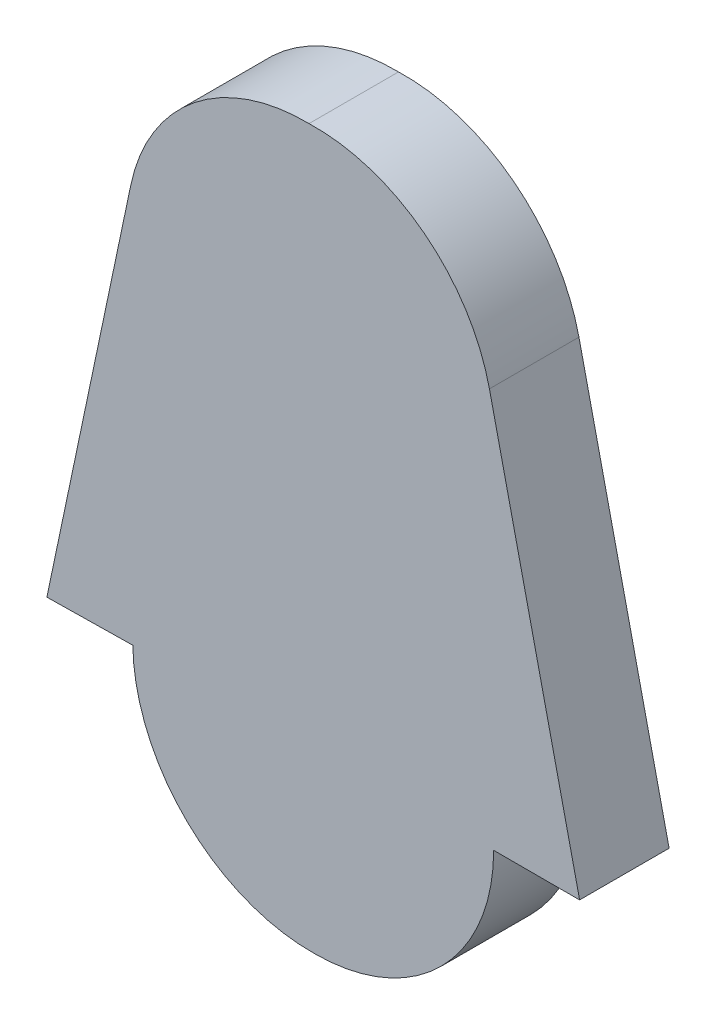
SolidWorks part; units mm, degrees
material "Plain Carbon Steel"
ref_plane "Front Plane" through (0, 0, 0) normal (0, 0, 1) x (1, 0, 0)
ref_plane "Top Plane" through (0, 0, 0) normal (0, 1, 0) x (1, 0, 0)
ref_plane "Right Plane" through (0, 0, 0) normal (1, 0, 0) x (0, 0, -1)
sketch "Sketch1" plane through (0, 0, 0) normal (0, 0, 1) x (1, 0, 0)
  line B0 (50.6598, -22.4809) -> (50.6598, -6.6059)
  line B1 (40.8052, -6.6059) -> (40.8052, -22.4809)
  line B2 (-11.4373, 39.0502) -> (-4.7473, 45.8293)
  line B3 (-4.7473, 45.8293) -> (-4.9808, 47.592)
  line B4 (-4.9808, 47.592) -> (-15.3046, 46.2245)
  line B5 (-15.3046, 46.2245) -> (-8.7339, -3.3803)
  line B6 (1.7621, -11.47) -> (46.5302, -5.8079)
  line B7 (45.5334, 6.8529) -> (5.0154, 5.583)
  line B8 (0.0223, 9.8219) -> (-2.4793, 28.7069)
  line B9 (-2.4793, 28.7069) -> (-10.7035, 33.5105)
  line B10 (-4.7473, 45.8293) -> (-2.4793, 28.7069)
  line B11 (-2.4793, 28.7069) -> (-0.2634, 29.0004)
  line B12 (-0.2634, 29.0004) -> (-2.1979, 43.6049)
  line B13 (-2.1979, 43.6049) -> (1.8812, 44.1452)
  line B14 (1.8812, 44.1452) -> (1.5477, 46.6632)
  line B15 (1.5477, 46.6632) -> (-4.7473, 45.8293)
  line B16 (55.1305, -12.1939) -> (51.9321, 1.9053)
  line B17 (37.5248, -6.9469) -> (36.3345, -12.1939)
  line B18 (36.3345, -12.1939) -> (39.3825, -12.1939)
  line B19 (52.0825, -12.1939) -> (55.1305, -12.1939)
  circle B20 centre (0, 0) radius 6.35
  arc B21 (-11.4373, 39.0502) -> (-10.7035, 33.5105) centre (-8.9193, 36.5653) ccw
  arc B22 (-8.7339, -3.3803) -> (1.7621, -11.47) centre (0.5828, -2.1462) ccw
  arc B23 (46.5302, -5.8079) -> (45.5334, 6.8529) centre (45.7325, 0.499) ccw
  arc B24 (0.0223, 9.8219) -> (5.0154, 5.583) centre (4.8624, 10.463) ccw
  arc B25 (39.3825, -12.1939) -> (52.0825, -12.1939) centre (45.7325, -12.1939) ccw
sketch_block_instance "Cam Geometry-1"
sketch_block "Cam Geometry"
sketch "Sketch2" plane through (0, 0, 0) normal (0, 0, 1) x (1, 0, 0)
  line L22 (55.1305, -12.1939) -> (51.9321, 1.9053) construction
  line L23 (52.0825, -12.1939) -> (55.1305, -12.1939) construction
  line L25 (55.1305, -12.1939) -> (51.9321, 1.9053)
  line L26 (52.0825, -12.1939) -> (55.1305, -12.1939)
  line L27 (36.2361, -12.3421) -> (39.213, 1.8056)
  line L28 (45.5334, 6.8529) -> (45.7325, -18.5439) construction
  line L29 (39.2837, -12.2943) -> (36.2361, -12.3421)
  arc A8 (46.5302, -5.8079) -> (45.5334, 6.8529) centre (45.7325, 0.499) ccw construction
  arc A9 (39.3825, -12.1939) -> (52.0825, -12.1939) centre (45.7325, -12.1939) ccw construction
  arc A10 (51.9321, 1.9053) -> (45.5334, 6.8529) centre (45.7325, 0.499) ccw
  arc A11 (45.7325, -18.5439) -> (52.0825, -12.1939) centre (45.7325, -12.1939) ccw
  arc A12 (39.213, 1.8056) -> (45.5334, 6.8529) centre (45.4339, 0.4966) cw
  arc A13 (45.7325, -18.5439) -> (39.2837, -12.2943) centre (45.6329, -12.1947) cw
extrude "Boss-Extrude1" add sketch "Sketch2" along normal mid plane 3.175
